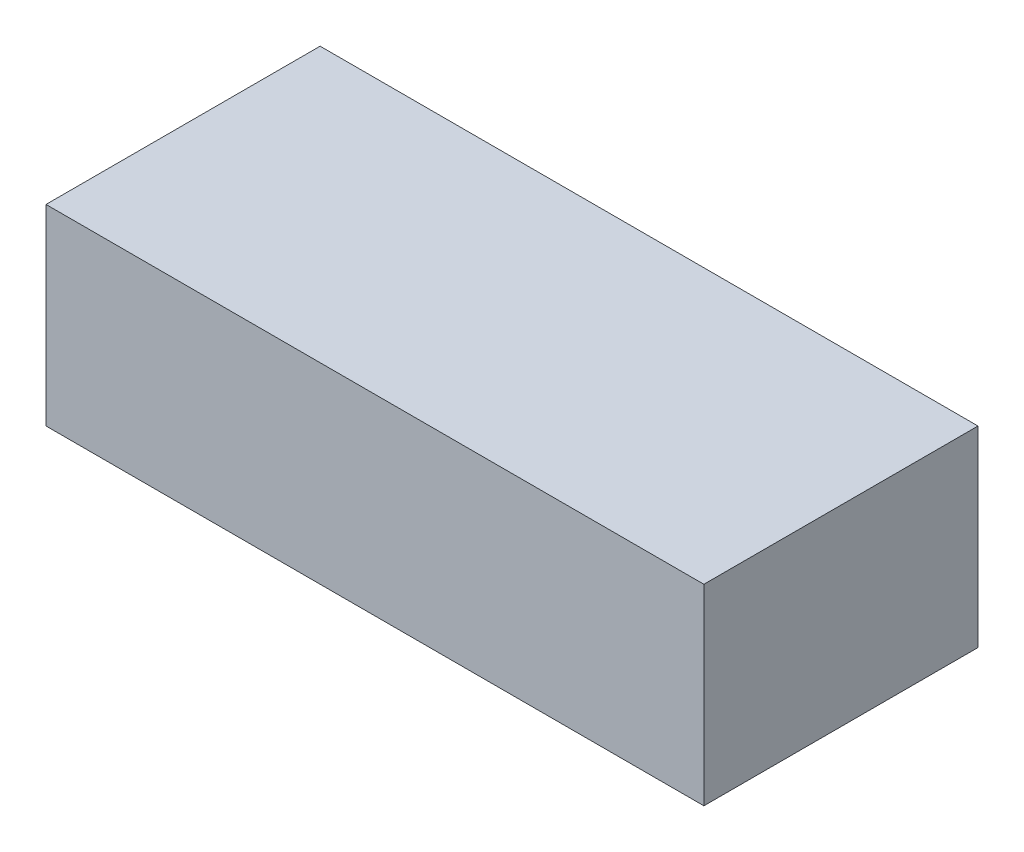
SolidWorks part; units mm, degrees
ref_plane "Front Plane" through (0, 0, 0) normal (0, 0, 1) x (1, 0, 0)
ref_plane "Top Plane" through (0, 0, 0) normal (0, 1, 0) x (1, 0, 0)
ref_plane "Right Plane" through (0, 0, 0) normal (1, 0, 0) x (0, 0, -1)
sketch "Sketch1" plane through (0, 0, 0) normal (0, 1, 0) x (1, 0, 0)
  line L1 (-54.9918, 0) -> (65.0082, 0)
  line L2 (-54.9918, 0) -> (-54.9918, 50)
  line L3 (-54.9918, 50) -> (65.0082, 50)
  line L4 (65.0082, 0) -> (65.0082, 50)
  dimension "D1" = 120
  dimension "D2" = 50
extrude "Boss-Extrude1" add sketch "Sketch1" along normal blind 15
sketch "Sketch2" plane through (0, 0, 0) normal (0, -1, 0) x (1, 0, 0)
  line L0 (-54.9918, -25) -> (65.0082, -25) construction
  line L1 (-54.9918, -50) -> (-54.9918, 0) construction
  line L2 (65.0082, 0) -> (65.0082, -50) construction
  line L3 (-30.9918, -25) -> (-30.9918, 0)
  line L4 (-54.9918, 0) -> (65.0082, 0) construction
  line L5 (-6.9918, -25) -> (-6.9918, 0)
  line L6 (17.0082, -25) -> (17.0082, 0)
  line L7 (41.0082, -25) -> (41.0082, 0)
  line L8 (-54.9918, 0) -> (-54.9918, -10)
  line L9 (-54.9918, -10) -> (65.0082, -10)
  line L10 (65.0082, -10) -> (65.0082, 0)
  line L11 (65.0082, 0) -> (-54.9918, 0)
  line L12 (-30.9918, -25) -> (-28.9918, -25)
  line L13 (-28.9918, -25) -> (-28.9918, -10)
  line L14 (-6.9918, -25) -> (-4.9935, -25)
  line L15 (-4.9935, -25) -> (-4.9935, -10)
  line L16 (17.0082, -25) -> (19.0082, -25)
  line L17 (19.0082, -25) -> (19.0082, -10)
  line L18 (41.0082, -25) -> (43.0082, -25)
  line L19 (43.0082, -25) -> (43.0082, -10)
  line L20 (43.0082, -10) -> (41.0082, -10)
  line L21 (19.0082, -10) -> (17.0082, -10)
  line L22 (-4.9935, -10) -> (-30.9918, -10)
  line M12 (-54.9918, 0) -> (-54.9918, -50)
  line M14 (65.0082, -50) -> (65.0082, 0)
  line M15 (65.0082, 0) -> (-54.9918, 0)
  dimension "D1" = 24
  dimension "D2" = 24
  dimension "D3" = 24
  dimension "D4" = 24
  dimension "D5" = 10
  dimension "D6" = 2
  dimension "D7" = 2
  dimension "D8" = 2
extrude "Boss-Extrude2" add sketch "Sketch2" along normal blind 20 contours L3 L9 L5 M15 | L9 L3 M12 M15 | L12 L13 L9 L3 | L14 L15 L9 L5 | L5 L9 L6 M15 | L6 L9 L7 M15 | L16 L17 L9 L6 | L7 L9 M14 M15 | L18 L19 L9 L7
sketch "Sketch3" plane through (0, 0, 0) normal (0, -1, 0) x (1, 0, 0)
  line L0 (-54.9918, -10) -> (-30.9918, -10)
  line L1 (-30.9918, -10) -> (-30.9918, -25)
  line L2 (-30.9918, -25) -> (-28.9918, -25)
  line L3 (-28.9918, -25) -> (-28.9918, -10)
  line L4 (-28.9918, -10) -> (-6.9918, -10)
  line L5 (-6.9918, -10) -> (-6.9918, -25)
  line L6 (-6.9918, -25) -> (-4.9935, -25)
  line L7 (-4.9935, -25) -> (-4.9935, -10)
  line L8 (-4.9935, -10) -> (17.0082, -10)
  line L9 (17.0082, -10) -> (17.0082, -25)
  line L10 (17.0082, -25) -> (19.0082, -25)
  line L11 (19.0082, -25) -> (19.0082, -10)
  line L12 (19.0082, -10) -> (41.0082, -10)
  line L13 (41.0082, -10) -> (41.0082, -25)
  line L14 (41.0082, -25) -> (43.0082, -25)
  line L15 (43.0082, -25) -> (43.0082, -10)
  line L16 (43.0082, -10) -> (65.0082, -10)
  line L17 (65.0082, -10) -> (65.0082, -50)
  line L18 (65.0082, -50) -> (-54.9918, -50)
  line L20 (-54.9918, -50) -> (-54.9918, -10)
extrude "Cut-Extrude1" cut sketch "Sketch3" against normal blind 10
sketch "Sketch4" plane through (0, 0, -25) normal (0, 0, -1) x (-1, 0, 0)
  line L1 (28.9918, 10) -> (30.9918, 10)
  line L2 (28.9918, 10) -> (28.9918, -20)
  line L3 (28.9918, -20) -> (30.9918, -20)
  line L4 (30.9918, 10) -> (30.9918, -20)
  line L5 (4.9935, 10) -> (6.9918, 10)
  line L6 (4.9935, 10) -> (4.9935, -20)
  line L7 (4.9935, -20) -> (6.9918, -20)
  line L8 (6.9918, 10) -> (6.9918, -20)
  line L9 (-19.0082, 10) -> (-17.0082, 10)
  line L10 (-19.0082, 10) -> (-19.0082, -20)
  line L11 (-19.0082, -20) -> (-17.0082, -20)
  line L12 (-17.0082, 10) -> (-17.0082, -20)
  line L13 (-43.0082, 10) -> (-41.0082, 10)
  line L14 (-43.0082, 10) -> (-43.0082, -20)
  line L15 (-43.0082, -20) -> (-41.0082, -20)
  line L16 (-41.0082, 10) -> (-41.0082, -20)
extrude "Boss-Extrude4" add sketch "Sketch4" along normal blind 40
sketch "Sketch5" plane through (0, 10, 0) normal (0, 1, 0) x (1, 0, 0)
  line L1 (-30.9918, 50) -> (43.0082, 50)
  line L2 (-30.9918, 50) -> (-30.9918, 65)
  line L3 (-30.9918, 65) -> (43.0082, 65)
  line L4 (43.0082, 50) -> (43.0082, 65)
extrude "Cut-Extrude2" cut sketch "Sketch5" against normal blind 30
sketch "Sketch6" plane through (0, -20, 0) normal (0, -1, 0) x (1, 0, 0)
  line L0 (-54.9918, 0) -> (-54.9918, -10) construction
  line L1 (65.0082, 0) -> (-54.9918, 0) construction
  line L2 (65.0082, -10) -> (65.0082, 0) construction
  circle A0 centre (-49.9918, -5) radius 3
  circle A1 centre (60.0082, -5) radius 3
  point P12 (0, 0)
  dimension "D1" = 6
  dimension "D2" = 6
  dimension "D3" = 5
  dimension "D4" = 5
  dimension "D5" = 5
  dimension "D6" = 5
extrude "Cut-Extrude3" cut sketch "Sketch6" against normal blind 5
sketch "Sketch7" plane through (0, 0, -10) normal (0, 0, -1) x (-1, 0, 0)
  line L0 (-65.0082, 10) -> (-43.0082, 10) construction
  line L1 (-65.0082, -20) -> (-62.5681, -20)
  line L2 (-65.0082, -20) -> (-65.0082, 10)
  line L3 (-65.0082, 10) -> (-62.5681, 10)
  line L4 (-62.5681, -20) -> (-62.5681, 10)
extrude "Boss-Extrude5" add sketch "Sketch7" along normal blind 40
sketch "Sketch8" plane through (0, 0, -10) normal (0, 0, -1) x (-1, 0, 0)
  line L0 (30.9918, 10) -> (54.9918, 10) construction
  line L1 (52.3769, 10) -> (54.9918, 10)
  line L2 (52.3769, 10) -> (52.3769, -20)
  line L3 (52.3769, -20) -> (54.9918, -20)
  line L4 (54.9918, 10) -> (54.9918, -20)
extrude "Boss-Extrude6" add sketch "Sketch8" along normal blind 40
sketch "Sketch9" plane through (0, 0, -50) normal (0, 0, -1) x (-1, 0, 0)
  line L0 (-65.0082, 15) -> (54.9918, 15) construction
  line L1 (54.9918, 15) -> (54.9918, -20) construction
  line L2 (-65.0082, 15) -> (-65.0082, -20) construction
  circle A0 centre (-62.5082, 12.5) radius 1.5
  circle A1 centre (52.4918, 12.5) radius 1.5
  dimension "D1" = 3
  dimension "D2" = 3
  dimension "D3" = 2.5
  dimension "D4" = 2.5
  dimension "D5" = 2.5
  dimension "D6" = 2.5
extrude "Cut-Extrude4" cut sketch "Sketch9" against normal blind 5
